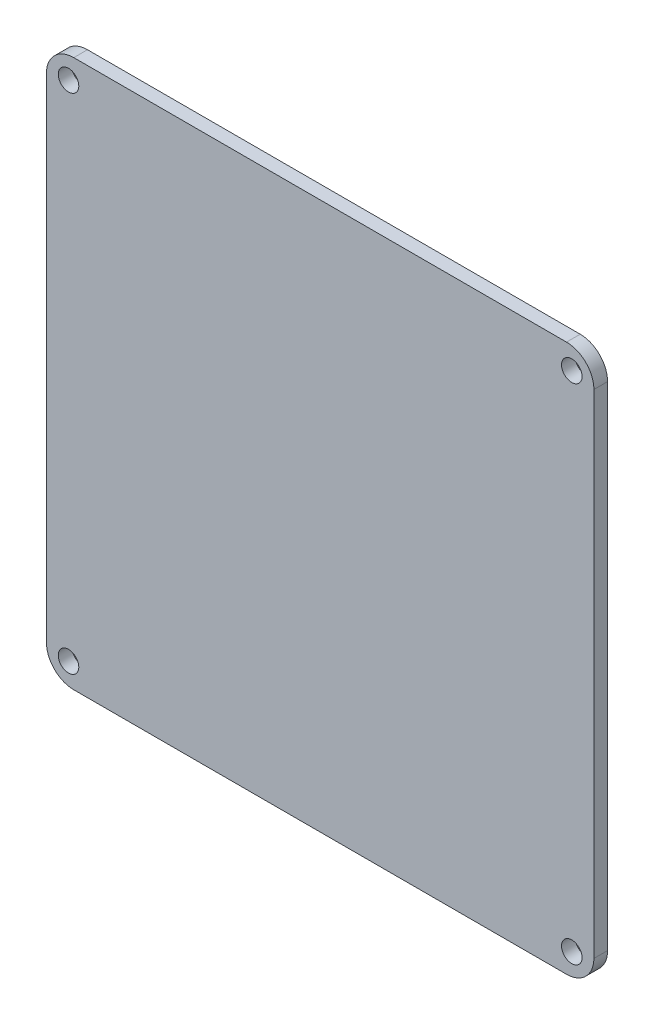
SolidWorks part; units mm, degrees
ref_plane "Front Plane" through (0, 0, 0) normal (0, 0, 1) x (1, 0, 0)
ref_plane "Top Plane" through (0, 0, 0) normal (0, 1, 0) x (1, 0, 0)
ref_plane "Right Plane" through (0, 0, 0) normal (1, 0, 0) x (0, 0, -1)
sketch "Sketch1" plane through (0, 0, 0) normal (0, 0, 1) x (1, 0, 0)
  line L1 (-90, -100) -> (90, -100)
  line L2 (-100, -90) -> (-100, 90)
  line L3 (-90, 100) -> (90, 100)
  line L4 (100, -90) -> (100, 90)
  line L5 (-100, -100) -> (100, 100) construction
  line L6 (-100, 100) -> (100, -100) construction
  circle A0 centre (-91.9239, 91.9239) radius 2
  circle A1 centre (91.9239, 91.9239) radius 2
  circle A2 centre (-91.9239, -91.9239) radius 2
  circle A3 centre (91.9239, -91.9239) radius 2
  arc A4 (-100, -90) -> (-90, -100) centre (-90, -90) ccw
  arc A5 (100, -90) -> (90, -100) centre (90, -90) cw
  arc A6 (90, 100) -> (100, 90) centre (90, 90) cw
  arc A7 (-90, 100) -> (-100, 90) centre (-90, 90) ccw
  point P0 (0, 0)
  dimension "D2" = 4
  dimension "D3" = 130
  dimension "D4" = 130
  dimension "D5" = 130
  dimension "D6" = 130
  dimension "D7" = 10
  dimension "D1" = 200
extrude "Boss-Extrude1" add sketch "Sketch1" along normal blind 5
sketch "Sketch2" plane through (0, 0, 5) normal (0, 0, 1) x (1, 0, 0)
  circle A0 centre (91.9239, 91.9239) radius 3.75
  circle A1 centre (-91.9239, 91.9239) radius 3.75
  circle A2 centre (-91.9239, -91.9239) radius 3.75
  circle A3 centre (91.9239, -91.9239) radius 3.75
  dimension "D1" = 7.5
extrude "Cut-Extrude1" cut sketch "Sketch2" against normal up to next
